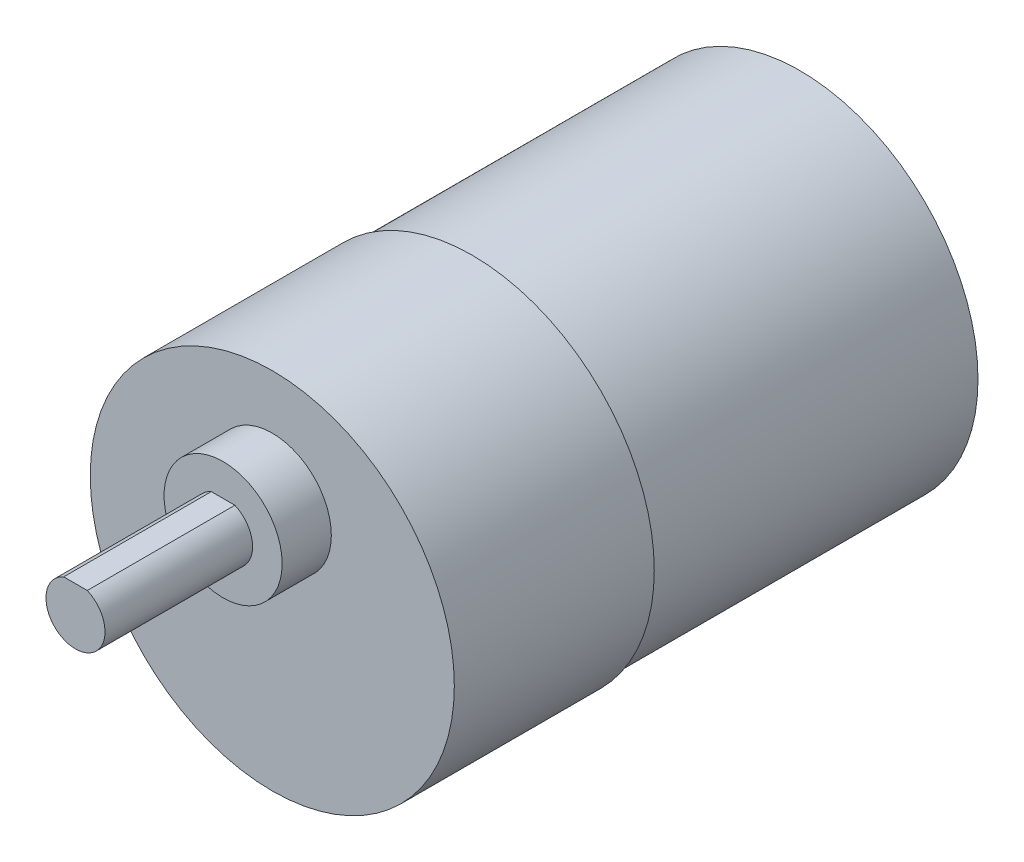
SolidWorks part; units mm, degrees
ref_plane "Front Plane" through (0, 0, 0) normal (0, 0, 1) x (1, 0, 0)
ref_plane "Top Plane" through (0, 0, 0) normal (0, 1, 0) x (1, 0, 0)
ref_plane "Right Plane" through (0, 0, 0) normal (1, 0, 0) x (0, 0, -1)
sketch "Sketch1" plane through (0, 0, 0) normal (0, 0, 1) x (1, 0, 0)
  circle A0 centre (0, 0) radius 18.1
  dimension "D1" = 36.2
extrude "Boss-Extrude1" add sketch "Sketch1" along normal mid plane 33.3
sketch "Sketch2" plane through (0, 0, 16.65) normal (0, 0, 1) x (1, 0, 0)
  circle A0 centre (0, 0) radius 18.5
  dimension "D1" = 37
extrude "Boss-Extrude2" add sketch "Sketch2" along normal blind 20.32
sketch "Sketch3" plane through (0, 0, 36.97) normal (0, 0, 1) x (1, 0, 0)
  line L0 (0, 0) -> (0, 7) construction
  circle A0 centre (0, 7) radius 6
  dimension "D1" = 7
  dimension "D2" = 12
extrude "Boss-Extrude3" add sketch "Sketch3" along normal blind 5
sketch "Sketch4" plane through (0, 0, 41.97) normal (0, 0, 1) x (1, 0, 0)
  circle A0 centre (0, 7) radius 3
  circle A1 centre (0, 7) radius 6 construction
  dimension "D1" = 6
extrude "Boss-Extrude4" add sketch "Sketch4" along normal blind 15
sketch "Sketch5" plane through (0, 0, 56.97) normal (0, 0, 1) x (1, 0, 0)
  line L0 (-1.199, 9.75) -> (1.199, 9.75)
  line L1 (-1.199, 9.75) -> (-1.199, 11.5192)
  line L2 (-1.199, 11.5192) -> (1.199, 11.5192)
  line L3 (1.199, 11.5192) -> (1.199, 9.75)
  circle A0 centre (0, 7) radius 3 construction
  circle A1 centre (0, 7) radius 3 construction
  dimension "D1" = 2.75
extrude "Cut-Extrude1" cut sketch "Sketch5" against normal up to surface (15 mm away) up to face at (3, 7, 41.97)
